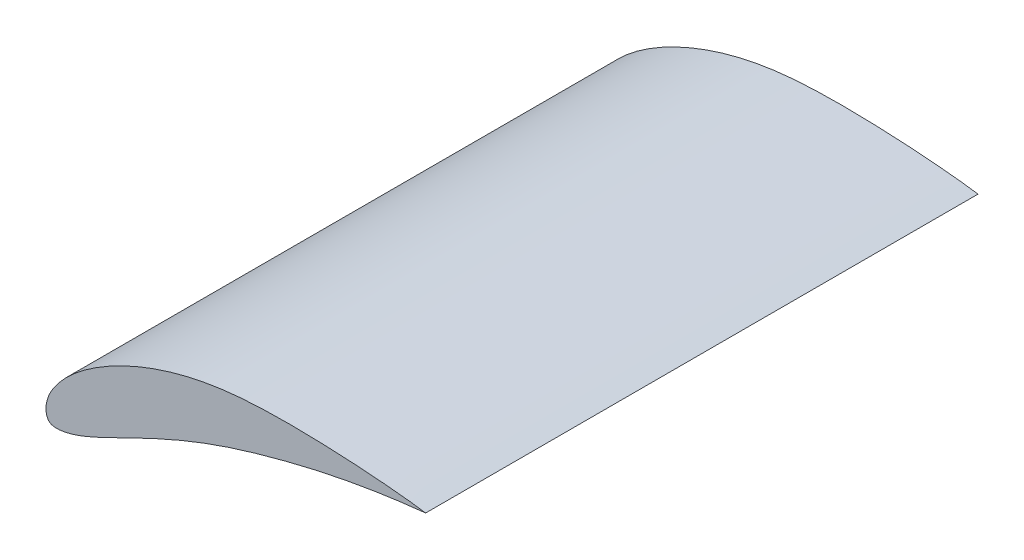
SolidWorks part; units mm, degrees
ref_plane "Front Plane" through (0, 0, 0) normal (0, 0, 1) x (1, 0, 0)
ref_plane "Top Plane" through (0, 0, 0) normal (0, 1, 0) x (1, 0, 0)
ref_plane "Right Plane" through (0, 0, 0) normal (1, 0, 0) x (0, 0, -1)
sketch "Sketch4" plane through (0, 0, 0) normal (0, 0, 1) x (1, 0, 0)
  line L0 (817.0431, 414.2854) -> (642.7309, 366.2771) construction
  line L1 (642.7309, 366.2771) -> (628.0016, 419.7574) construction
  spline S2 degree 3 poles (643.6437, 374.253) (644.0701, 375.2728) (644.5684, 376.2472) (645.666, 378.1321) (646.2647, 379.043) (647.542, 380.8143) (648.2218, 381.6769) (649.6399, 383.3519) (650.3742, 384.1592) (652.6377, 386.5087) (654.2277, 387.9781) (657.5268, 390.7746) (659.2368, 392.1005) (662.7548, 394.6353) (664.5641, 395.8443) (668.2636, 398.158) (670.1389, 399.253) (675.8312, 402.3788) (679.7131, 404.253) (687.6241, 407.6464) (691.6555, 409.1605) (697.8138, 411.1632) (699.885, 411.7864) (703.0191, 412.6554) (704.0683, 412.9342) (706.1758, 413.47) (707.2341, 413.7269) (712.5234, 414.9521) (716.768, 415.7466) (725.2812, 416.9941) (729.5501, 417.4443) (738.1081, 418.0591) (742.3965, 418.234) (750.9849, 418.4182) (755.285, 418.4268) (763.8944, 418.3127) (768.205, 418.1907) (776.8279, 417.846) (781.1357, 417.6238) (789.7445, 417.0846) (794.0455, 416.7693) (800.4912, 416.2156) (802.6388, 416.0174) (806.9312, 415.5844) (809.0772, 415.3507) (813.1661, 414.8509) (815.1098, 414.5945) (817.0431, 414.2854) knots 0.548291 0.548291 0.548291 0.548291 0.556103 0.556103 0.563916 0.563916 0.571728 0.571728 0.579541 0.579541 0.595166 0.595166 0.610791 0.610791 0.626416 0.626416 0.642041 0.642041 0.673291 0.673291 0.704541 0.704541 0.720166 0.720166 0.727978 0.727978 0.735791 0.735791 0.767041 0.767041 0.798291 0.798291 0.829541 0.829541 0.860791 0.860791 0.892041 0.892041 0.923291 0.923291 0.954541 0.954541 0.970166 0.970166 0.985791 0.985791 1 1 1 1
  spline S3 degree 3 poles (643.6437, 374.253) (643.6171, 374.1841) (643.5894, 374.1112) (643.5362, 373.9691) (643.4575, 373.7557) (643.3822, 373.5413) (643.2364, 373.1112) (643.1457, 372.8227) (642.895, 371.9512) (642.7562, 371.3624) (642.5483, 370.1656) (642.4805, 369.5617) (642.4385, 368.3568) (642.4608, 367.7538) (642.6377, 366.5459) (642.7944, 365.9598) (643.1041, 365.2646) (643.1721, 365.1266) (643.322, 364.861) (643.4039, 364.7333) (643.5798, 364.4862) (643.6733, 364.3667) (643.8825, 364.1433) (643.996, 364.0382) (644.2379, 363.8555) (644.3678, 363.7777) (644.639, 363.6395) (644.7801, 363.5775) (645.208, 363.4198) (645.5024, 363.3495) (646.0993, 363.2401) (646.4029, 363.2052) (647.0084, 363.1617) (647.3116, 363.1526) (647.9188, 363.1565) (648.2241, 363.1696) (648.8252, 363.2136) (649.1221, 363.2445) (650.0042, 363.3573) (650.581, 363.4593) (652.2946, 363.8052) (653.4121, 364.0947) (656.7174, 365.0761) (658.8602, 365.8745) (663.0946, 367.5928) (665.1839, 368.5181) (669.3327, 370.4397) (671.3918, 371.4368) (675.5005, 373.4537) (677.55, 374.4736) (681.6541, 376.5015) (683.7094, 377.5075) (689.8949, 380.4795) (694.0438, 382.401) (700.3171, 385.1644) (702.4163, 386.0663) (706.6327, 387.8274) (708.7507, 388.6868) (715.1255, 391.1886) (719.4064, 392.752) (728.0266, 395.6819) (732.3662, 397.0472) (741.0887, 399.632) (745.471, 400.8534) (754.2728, 403.1711) (758.6921, 404.2678) (767.5684, 406.3337) (772.0289, 407.3037) (780.9701, 409.0912) (785.4516, 409.9093) (794.4366, 411.3956) (798.9397, 412.0659) (807.965, 413.2752) (812.4873, 413.8134) (817.0275, 414.2838) (817.0353, 414.2846) (817.0431, 414.2854) knots 0 0 0 0 0.000488 0.000488 0.000977 0.001953 0.001953 0.003906 0.003906 0.007812 0.007812 0.011719 0.011719 0.015625 0.015625 0.019531 0.019531 0.020508 0.020508 0.021484 0.021484 0.022461 0.022461 0.023438 0.023438 0.024414 0.024414 0.025391 0.025391 0.027344 0.027344 0.029297 0.029297 0.03125 0.03125 0.033203 0.033203 0.035156 0.035156 0.039063 0.039063 0.046875 0.046875 0.0625 0.0625 0.078125 0.078125 0.09375 0.09375 0.109375 0.109375 0.125 0.125 0.15625 0.15625 0.171875 0.171875 0.1875 0.1875 0.21875 0.21875 0.25 0.25 0.28125 0.28125 0.3125 0.3125 0.34375 0.34375 0.375 0.375 0.40625 0.40625 0.4375 0.4375 0.437554 0.437554 0.437554 0.437554
  dimension "D1" = 180.8025
extrude "Boss-Extrude1" add sketch "Sketch4" along normal blind 254
ref_plane "Plane1" through (0, 0, 127) normal (0, 0, -1) x (-1, 0, 0)
sketch "Sketch6" plane through (0, 0, 127) normal (0, 0, -1) x (-1, 0, 0)
  line L0 (-658.7825, 307.9959) -> (-642.7309, 366.2771) construction
  line L1 (-642.7309, 366.2771) -> (-817.0431, 414.2854) construction
  spline S0 degree 3 poles (-643.6437, 374.253) (-643.6171, 374.1841) (-643.5894, 374.1112) (-643.5362, 373.9691) (-643.4575, 373.7557) (-643.3822, 373.5413) (-643.2364, 373.1112) (-643.1457, 372.8227) (-642.895, 371.9512) (-642.7562, 371.3624) (-642.5483, 370.1656) (-642.4805, 369.5617) (-642.4385, 368.3568) (-642.4608, 367.7538) (-642.6377, 366.5459) (-642.7944, 365.9598) (-643.1041, 365.2646) (-643.1721, 365.1266) (-643.322, 364.861) (-643.4039, 364.7333) (-643.5798, 364.4862) (-643.6733, 364.3667) (-643.8825, 364.1433) (-643.996, 364.0382) (-644.2379, 363.8555) (-644.3678, 363.7777) (-644.639, 363.6395) (-644.7801, 363.5775) (-645.208, 363.4198) (-645.5024, 363.3495) (-646.0993, 363.2401) (-646.4029, 363.2052) (-647.0084, 363.1617) (-647.3116, 363.1526) (-647.9188, 363.1565) (-648.2241, 363.1696) (-648.8252, 363.2136) (-649.1221, 363.2445) (-650.0042, 363.3573) (-650.581, 363.4593) (-652.2946, 363.8052) (-653.4121, 364.0947) (-656.7174, 365.0761) (-658.8602, 365.8745) (-663.0946, 367.5928) (-665.1839, 368.5181) (-669.3327, 370.4397) (-671.3918, 371.4368) (-675.5005, 373.4537) (-677.55, 374.4736) (-681.6541, 376.5015) (-683.7094, 377.5075) (-689.8949, 380.4795) (-694.0438, 382.401) (-700.3171, 385.1644) (-702.4163, 386.0663) (-706.6327, 387.8274) (-708.7507, 388.6868) (-715.1255, 391.1886) (-719.4064, 392.752) (-728.0266, 395.6819) (-732.3662, 397.0472) (-741.0887, 399.632) (-745.471, 400.8534) (-754.2728, 403.1711) (-758.6921, 404.2678) (-767.5684, 406.3337) (-772.0289, 407.3037) (-780.9701, 409.0912) (-785.4516, 409.9093) (-794.4366, 411.3956) (-798.9397, 412.0659) (-807.965, 413.2752) (-812.4873, 413.8134) (-817.0275, 414.2838) (-817.0353, 414.2846) (-817.0431, 414.2854) knots 0 0 0 0 0.000488 0.000488 0.000977 0.001953 0.001953 0.003906 0.003906 0.007812 0.007812 0.011719 0.011719 0.015625 0.015625 0.019531 0.019531 0.020508 0.020508 0.021484 0.021484 0.022461 0.022461 0.023438 0.023438 0.024414 0.024414 0.025391 0.025391 0.027344 0.027344 0.029297 0.029297 0.03125 0.03125 0.033203 0.033203 0.035156 0.035156 0.039063 0.039063 0.046875 0.046875 0.0625 0.0625 0.078125 0.078125 0.09375 0.09375 0.109375 0.109375 0.125 0.125 0.15625 0.15625 0.171875 0.171875 0.1875 0.1875 0.21875 0.21875 0.25 0.25 0.28125 0.28125 0.3125 0.3125 0.34375 0.34375 0.375 0.375 0.40625 0.40625 0.4375 0.4375 0.437554 0.437554 0.437554 0.437554 construction
  dimension "D1" = 180.8025
sketch "Sketch7" plane through (0, 0, 254) normal (0, 0, 1) x (1, 0, 0)
  line L0 (642.7309, 366.2771) -> (817.0431, 414.2854) construction
  line L1 (642.7309, 366.2771) -> (817.0431, 414.2854) construction
sketch "Sketch8" plane through (0, 0, 0) normal (0, 0, -1) x (-1, 0, 0)
  line L0 (-642.7309, 366.2771) -> (-817.0431, 414.2854) construction
  line L1 (-642.7309, 366.2771) -> (-817.0431, 414.2854) construction
